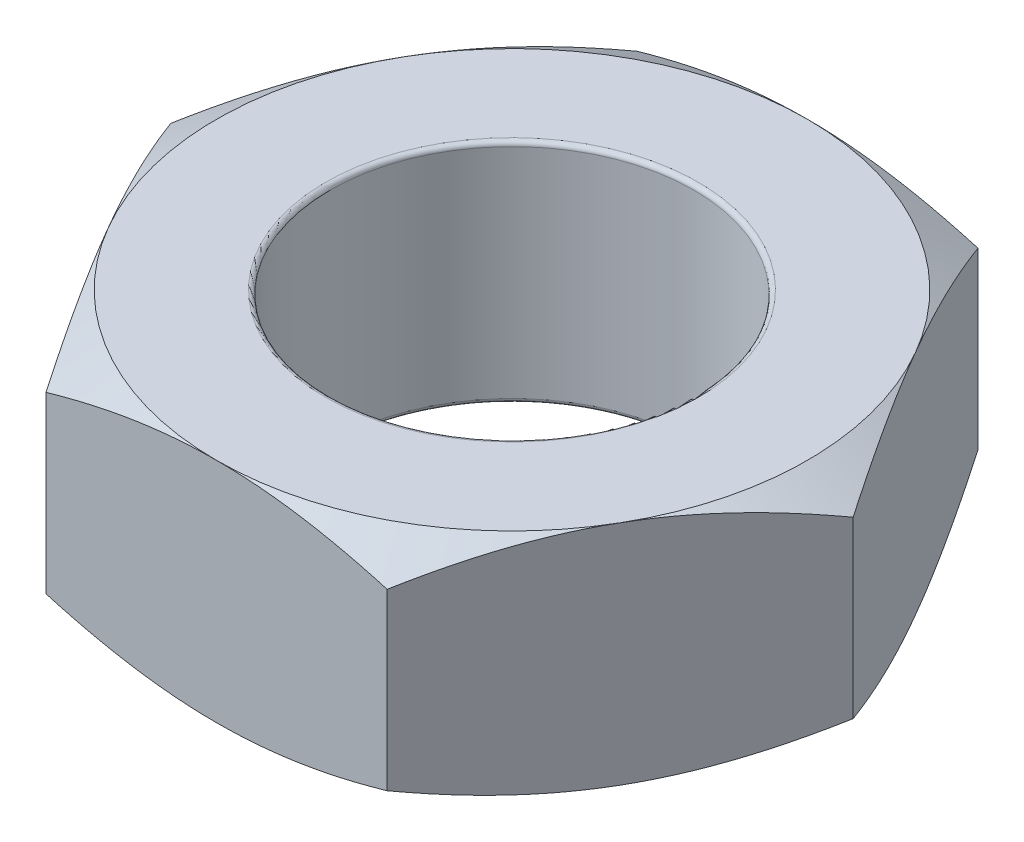
SolidWorks part; units mm, degrees
ref_plane "Front Plane" through (0, 0, 0) normal (0, 0, 1) x (1, 0, 0)
ref_plane "Top Plane" through (0, 0, 0) normal (0, 1, 0) x (1, 0, 0)
ref_plane "Right Plane" through (0, 0, 0) normal (1, 0, 0) x (0, 0, -1)
sketch "Sketch1" plane through (0, 0, 0) normal (0, 1, 0) x (1, 0, 0)
  line L1 (-1.8764, 0) -> (-0.9382, -1.625)
  line L2 (-0.9382, -1.625) -> (0.9382, -1.625)
  line L3 (0.9382, -1.625) -> (1.8764, 0)
  line L4 (1.8764, 0) -> (0.9382, 1.625)
  line L5 (0.9382, 1.625) -> (-0.9382, 1.625)
  line L6 (-0.9382, 1.625) -> (-1.8764, 0)
  circle A0 centre (0, 0) radius 1
  circle A1 centre (0, 0) radius 1.625 construction
  dimension "D1" = 2
  dimension "D2" = 3.25
extrude "Boss-Extrude3" add sketch "Sketch1" along normal blind 1.25
sketch "Sketch3" plane through (0, 1.25, 0) normal (0, 1, 0) x (1, 0, 0)
  circle A0 centre (0, 0) radius 1.625 construction
  circle A1 centre (0, 0) radius 1.625
extrude "Cut-Extrude1" cut sketch "Sketch3" against normal blind 1 draft 60 flip side to cut
sketch "Sketch4" plane through (0, 0, 0) normal (0, -1, 0) x (1, 0, 0)
  circle A1 centre (0, 0) radius 1.625
  circle A2 centre (0, 0) radius 1.625
  dimension "D1" = 0
extrude "Cut-Extrude2" cut sketch "Sketch4" against normal blind 1 draft 60 flip side to cut
fillet "Fillet1" radius 0.025 2 edges at (0, 0, 1) (0, 1.25, 1)
